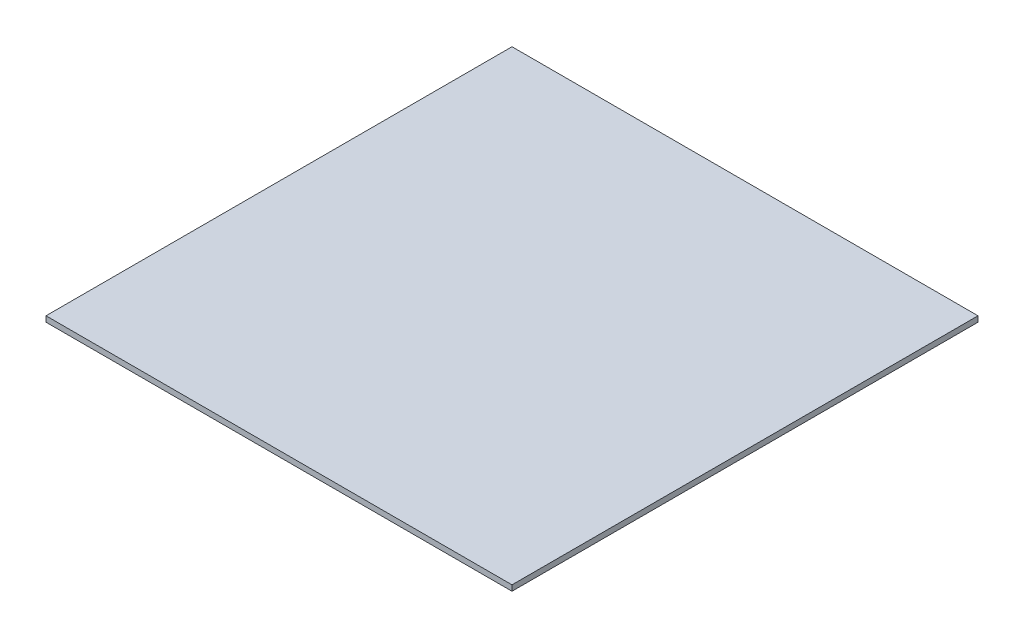
SolidWorks part; units mm, degrees
ref_plane "Front Plane" through (0, 0, 0) normal (0, 0, 1) x (1, 0, 0)
ref_plane "Top Plane" through (0, 0, 0) normal (0, 1, 0) x (1, 0, 0)
ref_plane "Right Plane" through (0, 0, 0) normal (1, 0, 0) x (0, 0, -1)
sketch "Sketch1" plane through (0, 0, 0) normal (0, 1, 0) x (1, 0, 0)
  line L1 (-125, -125) -> (125, -125)
  line L2 (-125, -125) -> (-125, 125)
  line L3 (-125, 125) -> (125, 125)
  line L4 (125, -125) -> (125, 125)
  line L5 (-125, -125) -> (125, 125) construction
  line L6 (-125, 125) -> (125, -125) construction
  point P0 (0, 0)
  dimension "D1" = 250
  dimension "D2" = 250
extrude "Boss-Extrude1" add sketch "Sketch1" along normal mid plane 3
